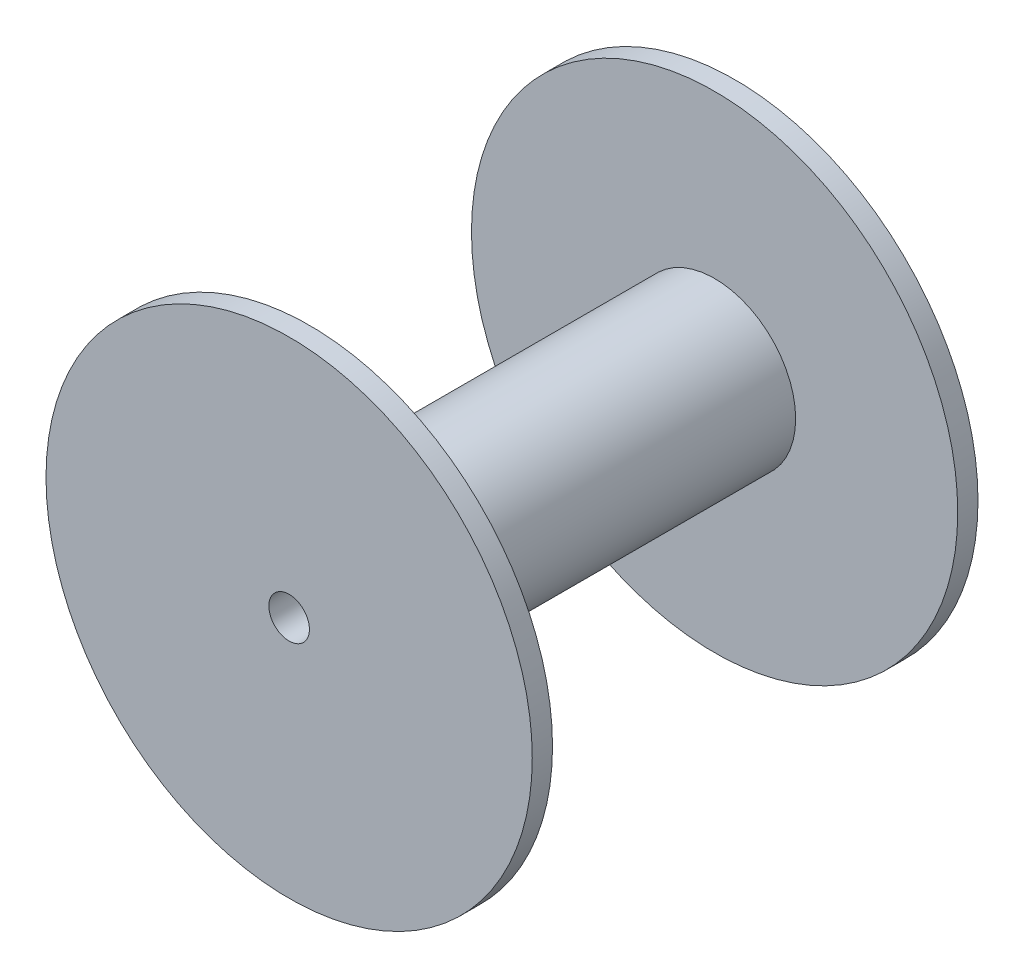
SolidWorks part; units mm, degrees
ref_plane "Front Plane" through (0, 0, 0) normal (0, 0, 1) x (1, 0, 0)
ref_plane "Top Plane" through (0, 0, 0) normal (0, 1, 0) x (1, 0, 0)
ref_plane "Right Plane" through (0, 0, 0) normal (1, 0, 0) x (0, 0, -1)
sketch "Sketch2" plane through (0, 0, 0) normal (0, 0, 1) x (1, 0, 0)
  circle A0 centre (0, 0) radius 200
  dimension "D1" = 400
extrude "Boss-Extrude1" add sketch "Sketch2" along normal blind 1000
sketch "Sketch3" plane through (0, 0, 1000) normal (0, 0, 1) x (1, 0, 0)
  circle A0 centre (0, 0) radius 600
  dimension "D1" = 1200
extrude "Boss-Extrude2" add sketch "Sketch3" along normal blind 50
sketch "Sketch4" plane through (0, 0, 0) normal (0, 0, -1) x (-1, 0, 0)
  circle A0 centre (0, 0) radius 600
  dimension "D1" = 1200
extrude "Boss-Extrude3" add sketch "Sketch4" along normal blind 50
sketch "Sketch5" plane through (0, 0, 1050) normal (0, 0, 1) x (1, 0, 0)
  circle A0 centre (0, 0) radius 50
  dimension "D1" = 100
extrude "Cut-Extrude1" cut sketch "Sketch5" against normal through all
